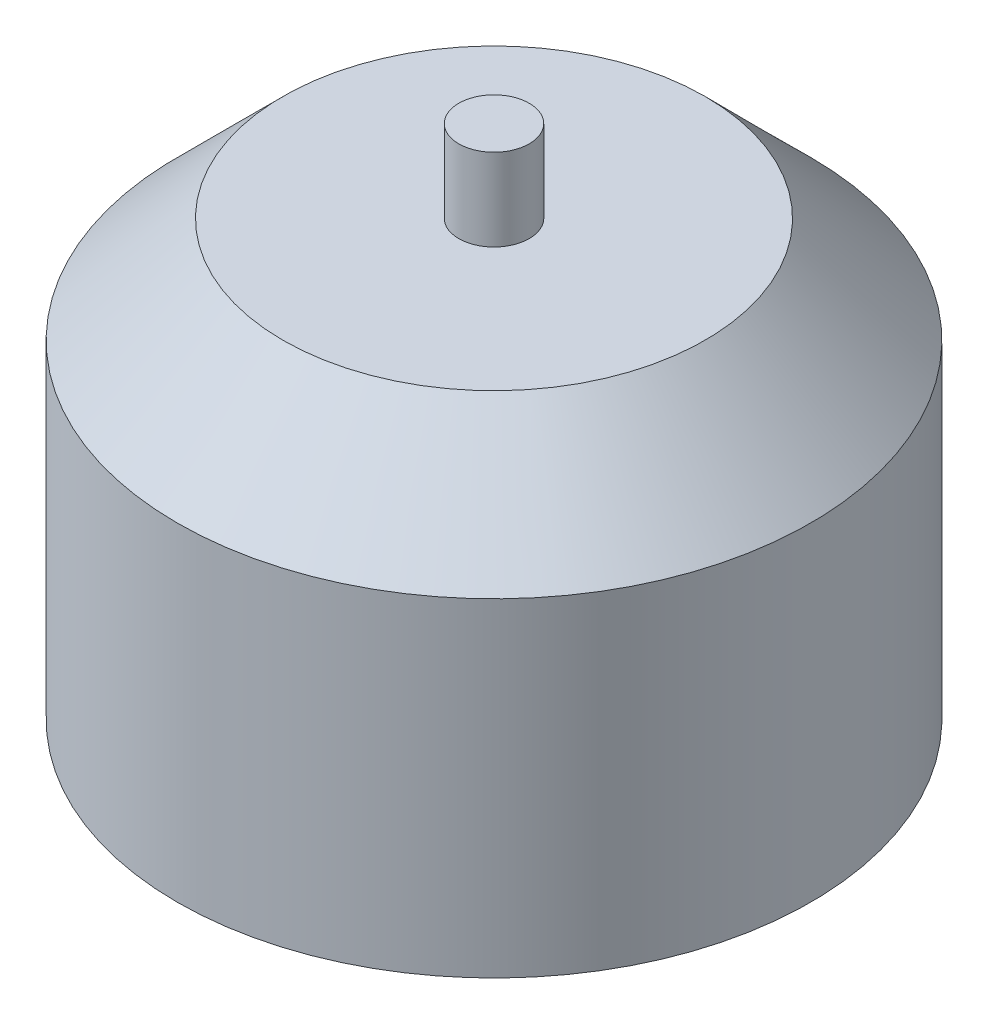
SolidWorks part; units mm, degrees
ref_plane "Front Plane" through (0, 0, 0) normal (0, 0, 1) x (1, 0, 0)
ref_plane "Top Plane" through (0, 0, 0) normal (0, 1, 0) x (1, 0, 0)
ref_plane "Right Plane" through (0, 0, 0) normal (1, 0, 0) x (0, 0, -1)
sketch "Sketch1" plane through (0, 0, 0) normal (0, 1, 0) x (1, 0, 0)
  circle A0 centre (0, 0) radius 13.5
  dimension "D1" = 27
extrude "Boss-Extrude1" add sketch "Sketch1" along normal blind 18.5
ref_axis "Axis1" through (0, 18.5, 0) along (0, -1, 0)
sketch "Sketch2" plane through (0, 0, 0) normal (0, 0, 1) x (1, 0, 0)
  line L0 (-13.5, 14) -> (-9, 18.5)
  line L1 (-13.5, 18.5) -> (-13.5, 0) construction
  line L2 (13.5, 18.5) -> (-13.5, 18.5) construction
  line L3 (-9, 18.5) -> (-13.5, 18.5)
  line L4 (-13.5, 18.5) -> (-13.5, 14)
  line L5 (-13.5, 0) -> (13.5, 0) construction
  dimension "D1" = 14
  dimension "D2" = 45
revolve "Cut-Revolve1" cut sketch "Sketch2" angle 360 about axis through (0, 18.5, 0) along (0, -1, 0)
sketch "Sketch3" plane through (0, 18.5, 0) normal (0, 1, 0) x (1, 0, 0)
  circle A0 centre (0, 0) radius 1.5
  dimension "D1" = 3
extrude "Boss-Extrude2" add sketch "Sketch3" along normal blind 3.5 and the other way offset from surface (21.5 mm away) 3 other way up to face at (0, 0, 13.5)
